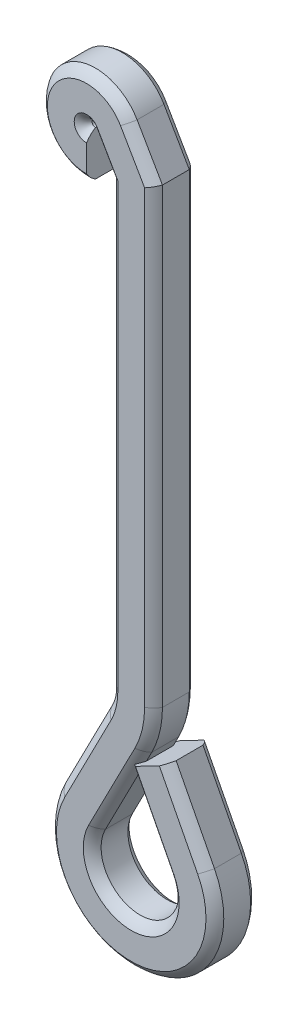
SolidWorks part; units mm, degrees
ref_plane "前基準面" through (0, 0, 0) normal (0, 0, 1) x (1, 0, 0)
ref_plane "上基準面" through (0, 0, 0) normal (0, 1, 0) x (1, 0, 0)
ref_plane "右基準面" through (0, 0, 0) normal (1, 0, 0) x (0, 0, -1)
sketch "草圖1" plane through (0, 0, 0) normal (0, 0, 1) x (1, 0, 0)
  line L0 (0, 1.2127) -> (0, 31.2127)
  line L1 (-1.5, 33.8108) -> (0, 31.2127)
  line L3 (-0.5556, -1.0779) -> (-3.665, -7.1111)
  line L4 (0, 0) -> (3.665, -7.1111) construction
  line L5 (0, -9) -> (-3.665, -7.1111) construction
  line L6 (3.665, -7.1111) -> (0, -9) construction
  line L7 (0, -9) -> (3.665, -7.1111) construction
  line L8 (-3.665, -7.1111) -> (3.665, -7.1111) construction
  line L9 (0, -9) -> (0, 0) construction
  line L10 (3.665, -7.1111) -> (1.088, -2.1111)
  line L12 (0, 31.2127) -> (-3, 31.2127) construction
  line L13 (-1.5, 33.8108) -> (-1.5, 31.2127) construction
  arc A0 (-3.665, -7.1111) -> (3.665, -7.1111) centre (0, -9) ccw
  arc A1 (-1.5, 33.8108) -> (-3, 31.2127) centre (-3, 32.9447) ccw
  arc A3 (0, 1.2127) -> (-0.5556, -1.0779) centre (-5, 1.2127) cw
  dimension "D1" = 60
  dimension "D5" = 5
  dimension "D2" = 120
  dimension "D3" = 3
  dimension "D4" = 9
  dimension "D6" = 8
  dimension "D7" = 30
  dimension "D8" = 5
ref_plane "平面1" through (-3, 31.2127, 0) normal (1, 0, 0) x (0, 0, -1)
sketch "草圖3" plane through (-3, 31.2127, 0) normal (1, 0, 0) x (0, 0, -1)
  line L0 (0, 3.4641) -> (0, 0) construction
  line L1 (0, 2.5981) -> (0, 0) construction
  line L2 (-0.9014, 1.5) -> (-1.5, 1.5) construction
  line L3 (-0.9014, 1.5) -> (0.9014, 1.5)
  line L4 (-1.5, 0.9014) -> (-1.5, -0.9014)
  line L5 (-0.9014, -1.5) -> (0.9014, -1.5)
  line L6 (1.5, 0.9014) -> (1.5, -0.9014)
  line L7 (-1.2374, 1.2374) -> (1.2374, -1.2374) construction
  line L8 (-1.2374, -1.2374) -> (1.2374, 1.2374) construction
  line L9 (-1.5, 1.5) -> (-1.5, 0.9014) construction
  line L10 (-1.5, -0.9014) -> (-1.5, -1.5) construction
  line L11 (-1.5, -1.5) -> (-0.9014, -1.5) construction
  line L12 (0.9014, -1.5) -> (1.5, -1.5) construction
  line L13 (1.5, -1.5) -> (1.5, -0.9014) construction
  line L14 (1.5, 0.9014) -> (1.5, 1.5) construction
  line L15 (1.5, 1.5) -> (0.9014, 1.5) construction
  line L16 (1.5, 1.5) -> (1.2374, 1.2374) construction
  line L18 (-1.2374, 1.2374) -> (-1.5, 1.5) construction
  line L19 (1.2374, -1.2374) -> (1.5, -1.5) construction
  line L20 (-1.2374, -1.2374) -> (-1.5, -1.5) construction
  arc A0 (-0.9014, 1.5) -> (-1.5, 0.9014) centre (0, 0) ccw
  arc A1 (-1.5, -0.9014) -> (-0.9014, -1.5) centre (0, 0) ccw
  arc A2 (1.5, 0.9014) -> (0.9014, 1.5) centre (0, 0) ccw
  arc A3 (0.9014, -1.5) -> (1.5, -0.9014) centre (0, 0) ccw
  dimension "D1" = 3.5
  dimension "D2" = 3
sweep "掃出1" add profiles "草圖3" path "草圖1"
